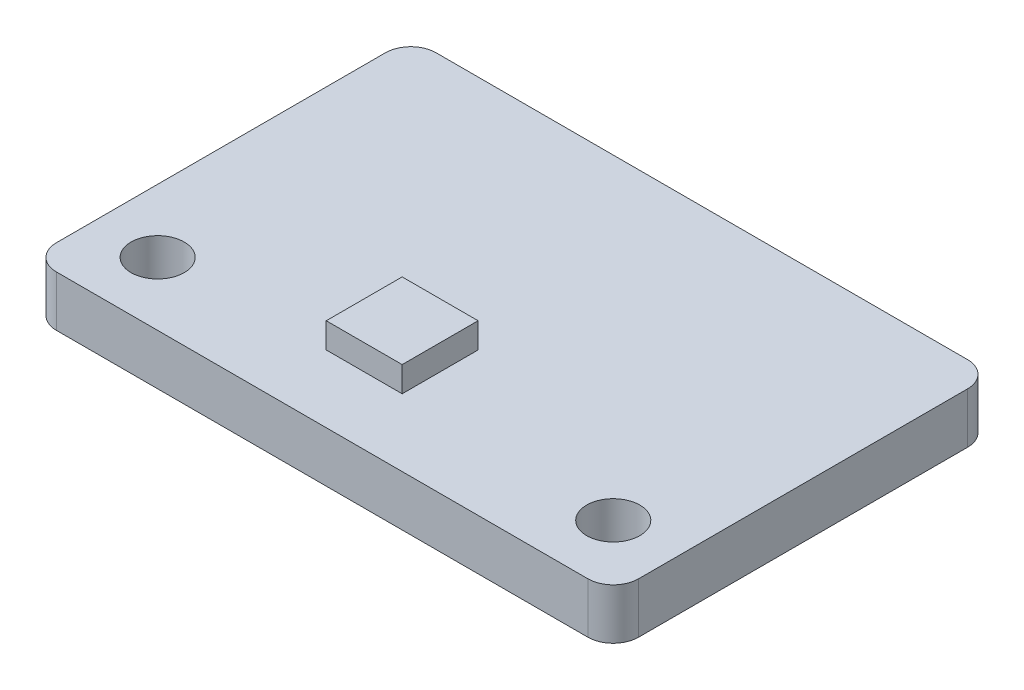
SolidWorks part; units mm, degrees
ref_plane "前视基准面" through (0, 0, 0) normal (0, 0, 1) x (1, 0, 0)
ref_plane "上视基准面" through (0, 0, 0) normal (0, 1, 0) x (1, 0, 0)
ref_plane "右视基准面" through (0, 0, 0) normal (1, 0, 0) x (0, 0, -1)
sketch "草图1" plane through (0, 0, 0) normal (0, 1, 0) x (1, 0, 0)
  line L0 (2.5, 2.5) -> (20.5, 2.5) construction
  line L1 (1, 0) -> (22, 0)
  line L2 (0, 1) -> (0, 14)
  line L3 (1, 15) -> (22, 15)
  line L4 (23, 1) -> (23, 14)
  line L5 (11.5, 15) -> (11.5, 0) construction
  circle A0 centre (2.5, 2.5) radius 1.05
  circle A1 centre (20.5, 2.5) radius 1.05
  arc A2 (0, 14) -> (1, 15) centre (1, 14) cw
  arc A3 (22, 15) -> (23, 14) centre (22, 14) cw
  arc A4 (22, 0) -> (23, 1) centre (22, 1) ccw
  arc A5 (1, 0) -> (0, 1) centre (1, 1) cw
  point P15 (0, 15)
  point P18 (23, 15)
  point P23 (0, 0)
  dimension "D3" = 18
  dimension "D5" = 2.1
  dimension "D6" = 1
  dimension "D1" = 15
  dimension "D2" = 23
  dimension "D4" = 2.5
extrude "凸台-拉伸1" add sketch "草图1" along normal blind 2
sketch "草图2" plane through (0, 2, 0) normal (0, 1, 0) x (1, 0, 0)
  line L0 (11.5, 15) -> (11.5, 0) construction
  line L1 (9, 5.6605) -> (12, 5.6605)
  line L2 (9, 5.6605) -> (9, 2.6605)
  line L3 (9, 2.6605) -> (12, 2.6605)
  line L4 (12, 5.6605) -> (12, 2.6605)
  line L5 (22, 15) -> (1, 15) construction
  line L6 (1, 0) -> (22, 0) construction
  line L7 (10.5, 5.6605) -> (10.5, 2.6605) construction
  dimension "D1" = 3
  dimension "D2" = 1
extrude "凸台-拉伸2" add sketch "草图2" along normal blind 1
